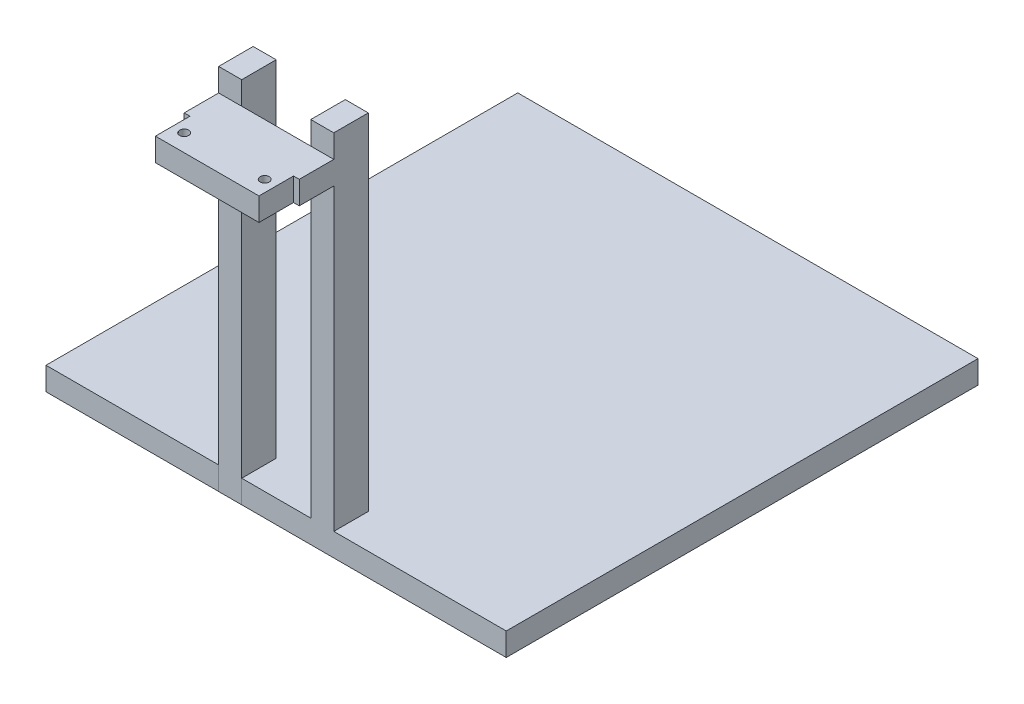
SolidWorks part; units mm, degrees
ref_plane "Front Plane" through (0, 0, 0) normal (0, 0, 1) x (1, 0, 0)
ref_plane "Top Plane" through (0, 0, 0) normal (0, 1, 0) x (1, 0, 0)
ref_plane "Right Plane" through (0, 0, 0) normal (1, 0, 0) x (0, 0, -1)
sketch "Sketch2" plane through (0, 0, 0) normal (0, 1, 0) x (1, 0, 0)
  line L1 (-100, 102.5) -> (100, 102.5)
  line L2 (-100, 102.5) -> (-100, -102.5)
  line L3 (-100, -102.5) -> (100, -102.5)
  line L4 (100, 102.5) -> (100, -102.5)
  line L5 (-100, 102.5) -> (100, -102.5) construction
  line L6 (-100, -102.5) -> (100, 102.5) construction
  point P0 (0, 0)
  dimension "D1" = 200
  dimension "D2" = 205
extrude "Boss-Extrude1" add sketch "Sketch2" along normal blind 10
sketch "Sketch3" plane through (0, 0, 0) normal (0, 1, 0) x (1, 0, 0)
  line L0 (-14.9476, -102.5) -> (15.0524, -102.5)
  line L1 (-100, -102.5) -> (100, -102.5) construction
  line L2 (0.0524, -102.5) -> (0, 0) construction
  line L3 (15.0524, -102.5) -> (25.0524, -102.5)
  line L4 (15.0524, -102.5) -> (15.0524, -87.5)
  line L5 (15.0524, -87.5) -> (25.0524, -87.5)
  line L6 (25.0524, -102.5) -> (25.0524, -87.5)
  line L7 (-14.9476, -102.5153) -> (-24.9476, -102.5256)
  line L8 (-24.9476, -102.5256) -> (-24.9629, -87.5256)
  line L9 (-14.9629, -87.5153) -> (-24.9629, -87.5256)
  line L10 (-14.9476, -102.5153) -> (-14.9629, -87.5153)
  point P5 (0.0524, -102.5)
  dimension "D1" = 30
  dimension "D2" = 10
  dimension "D3" = 15
extrude "Boss-Extrude3" add sketch "Sketch3" along normal blind 160 contours L7 L10 L9 L8 | L3 L6 L5 L4
ref_plane "Plane1" through (0, 0, 102.5) normal (0, 0, 1) x (1, 0, 0)
sketch "Sketch8" plane through (0, 0, 102.5) normal (0, 0, 1) x (1, 0, 0)
  line L1 (25.0524, 160) -> (25.0524, 10) construction
  line L5 (-24.9476, 160) -> (-24.9476, 0) construction
  line L8 (25.0524, 150) -> (25.0524, 140)
  line L9 (-24.9476, 140) -> (-24.9476, 150)
  line L11 (-24.9476, 150) -> (-24.9476, 140)
  line L14 (-24.9476, 150) -> (-24.9476, 140)
  line L16 (-24.9476, 150) -> (25.0524, 150)
  line L17 (-24.9476, 150) -> (-24.9476, 140)
  line L18 (-24.9476, 140) -> (25.0524, 140)
  point P22 (0.0524, 150)
  dimension "D2" = 10
extrude "Boss-Extrude4" add sketch "Sketch8" along normal blind 15 contours L9 L18 L8 L16
ref_plane "Plane2" through (0, 0, 117.5) normal (0, 0, 1) x (1, 0, 0)
sketch "Sketch9" plane through (0, 0, 117.5) normal (0, 0, 1) x (1, 0, 0)
  line L0 (0.0524, 150) -> (22.5524, 150)
  line L3 (-24.9476, 150) -> (25.0524, 150) construction
  line L4 (15.0524, 150) -> (25.0524, 150) construction
  line L5 (0.0524, 150) -> (-22.4476, 150)
  line L6 (-14.9476, 150) -> (-24.9476, 150) construction
  line L7 (-22.4476, 150) -> (-22.4476, 140)
  line L8 (-14.9476, 140) -> (-24.9476, 140) construction
  line L9 (-22.4476, 140) -> (22.5524, 140)
  line L10 (15.0524, 140) -> (25.0524, 140) construction
  line L11 (22.5524, 140) -> (22.5524, 150)
  dimension "D1" = 22.5
  dimension "D2" = 22.5
extrude "Boss-Extrude5" add sketch "Sketch9" along normal blind 15
ref_plane "Plane4" through (0, 150, 0) normal (0, 1, 0) x (1, 0, 0)
sketch "Sketch10" plane through (0, 150, 0) normal (0, 1, 0) x (1, 0, 0)
  circle A0 centre (17.5524, -125) radius 2
  circle A1 centre (-17.4476, -125) radius 2
  point P0 (0, 0)
  point P9 (0.0524, -125)
  dimension "D2" = 4
  dimension "D3" = 4
  dimension "D1" = 35
extrude "Cut-Extrude1" cut sketch "Sketch10" against normal blind 10
